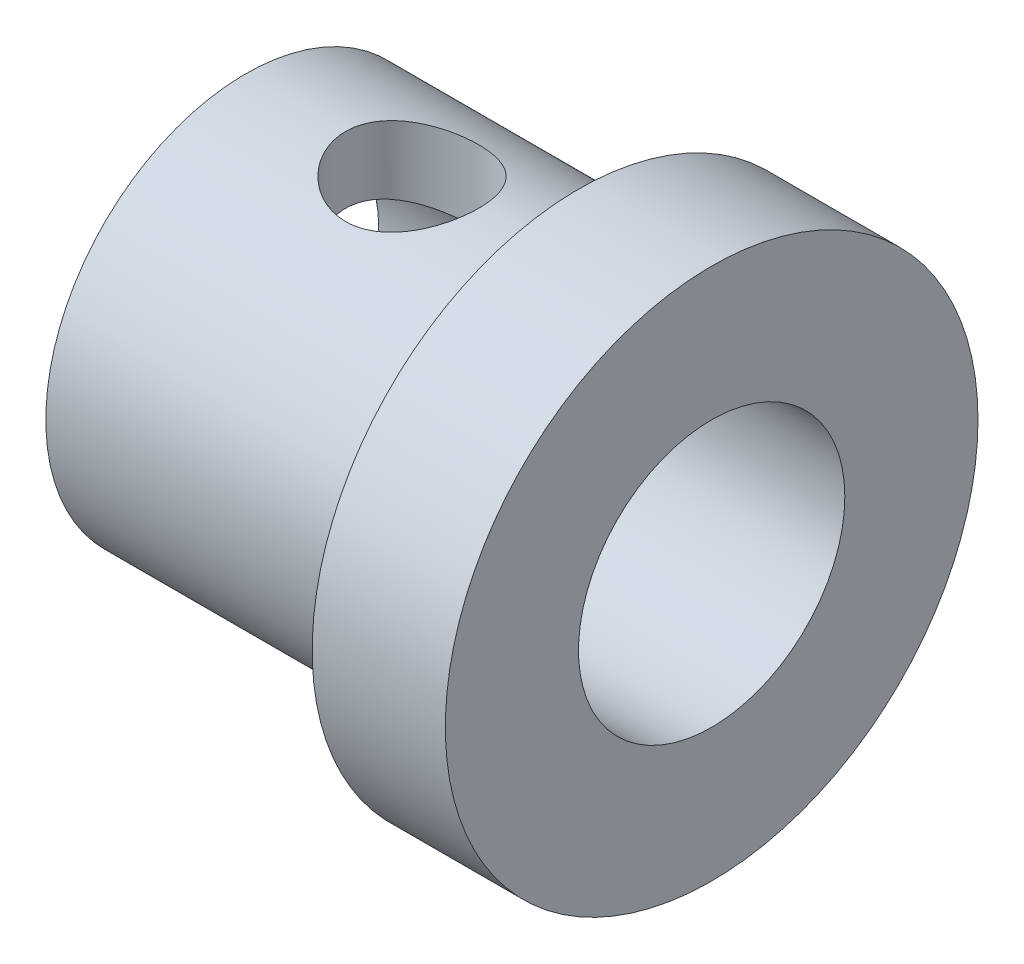
SolidWorks part; units mm, degrees
ref_plane "Front Plane" through (0, 0, 0) normal (0, 0, 1) x (1, 0, 0)
ref_plane "Top Plane" through (0, 0, 0) normal (0, 1, 0) x (1, 0, 0)
ref_plane "Right Plane" through (0, 0, 0) normal (1, 0, 0) x (0, 0, -1)
sketch "Sketch1" plane through (0, 0, 0) normal (1, 0, 0) x (0, 0, -1)
  circle A0 centre (0, 0) radius 3
  dimension "D1" = 6
extrude "Boss-Extrude1" add sketch "Sketch1" along normal mid plane 7
sketch "Sketch2" plane through (3.5, 0, 0) normal (1, 0, 0) x (0, 0, -1)
  circle A0 centre (0, 0) radius 4
  dimension "D1" = 8
extrude "Boss-Extrude2" add sketch "Sketch2" against normal blind 2
sketch "Sketch3" plane through (3.5, 0, 0) normal (1, 0, 0) x (0, 0, -1)
  circle A0 centre (0, 0) radius 2
  dimension "D1" = 4
extrude "Cut-Extrude1" cut sketch "Sketch3" against normal through all
sketch "Sketch4" plane through (0, 0, 0) normal (0, 1, 0) x (1, 0, 0)
  line L0 (-3.5, 3) -> (-3.5, -3) construction
  circle A0 centre (-1, 0) radius 1
  dimension "D2" = 2
  dimension "D1" = 2.5
extrude "Cut-Extrude2" cut sketch "Sketch4" against normal through all both and the other way through all
